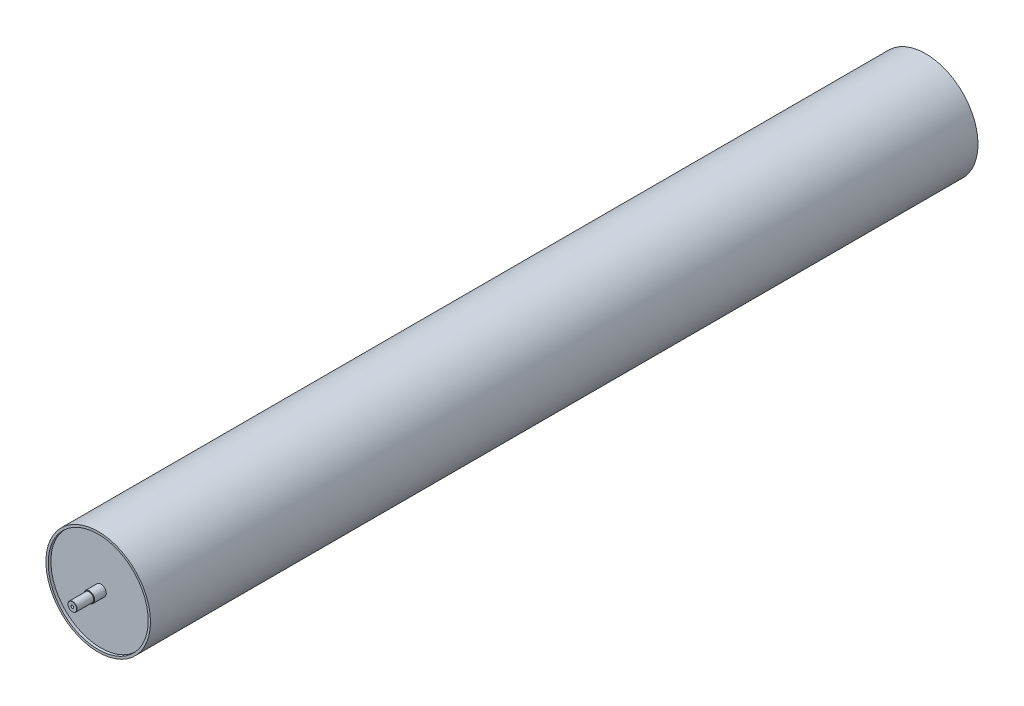
SolidWorks part; units mm, degrees
ref_plane "Front Plane" through (0, 0, 0) normal (0, 0, 1) x (1, 0, 0)
ref_plane "Top Plane" through (0, 0, 0) normal (0, 1, 0) x (1, 0, 0)
ref_plane "Right Plane" through (0, 0, 0) normal (1, 0, 0) x (0, 0, -1)
sketch "Sketch1" plane through (0, 0, 0) normal (0, 0, 1) x (1, 0, 0)
  circle A0 centre (0, 0) radius 98.5 construction
  circle A1 centre (0, 0) radius 92.76
  circle A2 centre (0, 0) radius 97
  dimension "D1" = 197
  dimension "D2" = 5.74
  dimension "D3" = 1.5
  dimension "D4" = 194
extrude "Boss-Extrude1" add sketch "Sketch1" along normal mid plane 1535
sketch "Sketch2" plane through (0, 0, 767.5) normal (0, 0, 1) x (1, 0, 0)
  circle A0 centre (0, 0) radius 92.76 construction
  circle A1 centre (0, 0) radius 92.76
extrude "Boss-Extrude2" add sketch "Sketch2" along normal blind 5 from offset 10 offset against normal yes
sketch "Sketch5" plane through (0, 0, 0) normal (1, 0, 0) x (0, 0, -1)
  line L0 (-784.5, 10) -> (784.5, 10)
  line L1 (784.5, 10) -> (784.5, 8.5)
  line L2 (784.5, 8.5) -> (815.5, 8.5)
  line L3 (815.5, 8.5) -> (815.5, 0)
  line L8 (815.5, 0) -> (-815.5, 0)
  line L9 (-815.5, 0) -> (-815.5, 8.5)
  line L14 (-815.5, 8.5) -> (-784.5, 8.5)
  line L15 (-784.5, 8.5) -> (-784.5, 10)
  line L16 (815.5, 0) -> (824, 0) construction
  line L18 (767.5, -97) -> (767.5, 97) construction
  point P20 (0, 10)
  dimension "D3" = 17
  dimension "D5" = 17
  dimension "D6" = 31
  dimension "D7" = 20
revolve "Revolve1" add sketch "Sketch5" angle 360 about L16
chamfer "Chamfer1" distance 0.5 4 edges at (0, -10, 784.5) (0, -10, -784.5) (0, -8.5, -815.5) (0, -8.5, 815.5)
hole_wizard "M6 Tapped Hole1" positions "Sketch6" profile "Sketch7" tap size "M6" standard "ISO"
sketch "Sketch6" plane through (0, 0, 815.5) normal (0, 0, 1) x (1, 0, 0)
  point P0 (0, 0)
sketch "Sketch7" plane through (0, 0, 815.5) normal (1, 0, 0) x (0, -1, 0)
  line L0 (0, 0) -> (0, 16.5022)
  line L1 (0, 16.5022) -> (2.5, 15)
  line L2 (2.5, 15) -> (2.5, 0)
  line L5 (2.5, 0) -> (0, 0)
  line L10 (0, 16.5022) -> (-2.5, 15) construction
  line L11 (0, -6.35) -> (0, 107.95) construction
  dimension "Tap Drill Dia." = 5
  dimension "Tap Drill Depth" = 15
  dimension "Drill Angle" = 118
cosmetic thread "Hole Thread1" parameters "D1"=12, "D2"=6
mirror "Mirror3" about plane through (0, 0, 0) normal (0, 0, 1) of "M6 Tapped Hole1", "Boss-Extrude2"
